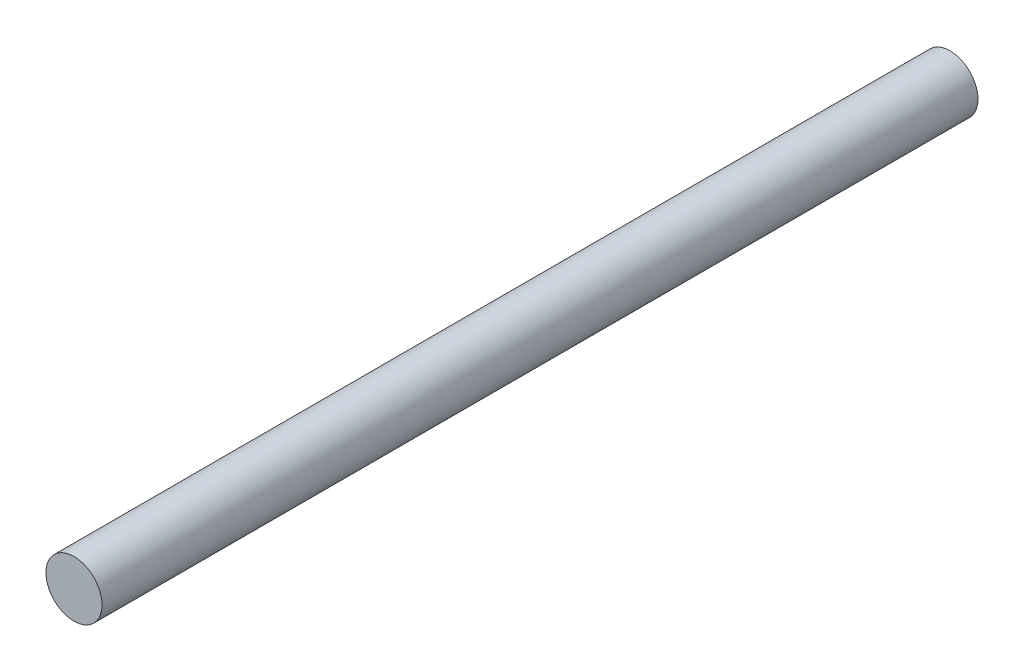
SolidWorks part; units mm, degrees
ref_plane "Front Plane" through (0, 0, 0) normal (0, 0, 1) x (1, 0, 0)
ref_plane "Top Plane" through (0, 0, 0) normal (0, 1, 0) x (1, 0, 0)
ref_plane "Right Plane" through (0, 0, 0) normal (1, 0, 0) x (0, 0, -1)
sketch "Sketch1" plane through (0, 0, 0) normal (0, 0, 1) x (1, 0, 0)
  circle A0 centre (0, 0) radius 8
  dimension "D1" = 16
extrude "Boss-Extrude1" add sketch "Sketch1" along normal blind 250
